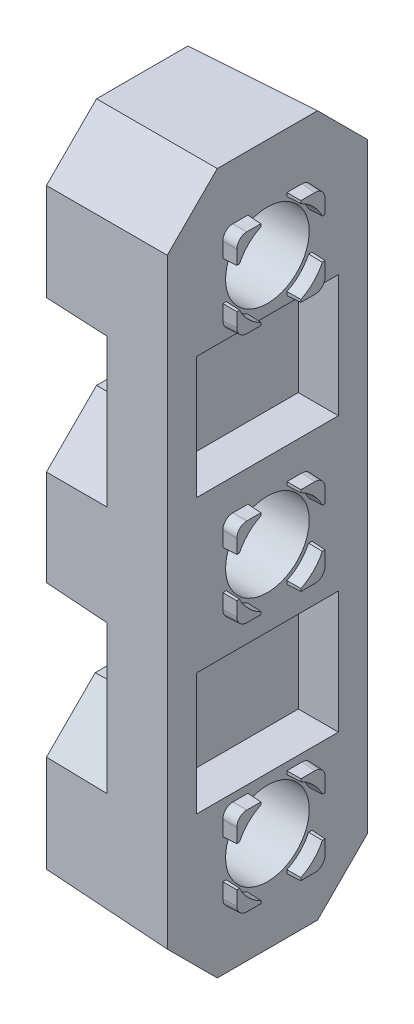
SolidWorks part; units mm, degrees
ref_plane "Front Plane" through (0, 0, 0) normal (0, 0, 1) x (1, 0, 0)
ref_plane "Top Plane" through (0, 0, 0) normal (0, 1, 0) x (1, 0, 0)
ref_plane "Right Plane" through (0, 0, 0) normal (1, 0, 0) x (0, 0, -1)
ref_plane "Plane1" through (88.9762, 0, 0) normal (1, 0, 0) x (0, 0, -1)
sketch "Sketch1" plane through (88.9762, 0, 0) normal (1, 0, 0) x (0, 0, -1)
  line L0 (7.8417, 8.8578) -> (17.5583, 8.8578)
  line L1 (17.5583, 8.8578) -> (17.5583, 43.9743)
  line L2 (17.5583, 43.9743) -> (7.8417, 43.9743)
  line L3 (7.8417, 43.9743) -> (7.8417, 8.8578)
extrude "Boss-Extrude1" add sketch "Sketch1" against normal blind 6.35
sketch "Sketch2" plane through (82.6262, 0, 0) normal (-1, 0, 0) x (0, 0, 1)
  line L0 (-7.8417, 36.5093) -> (-10.3153, 34.0358)
  line L1 (-10.3153, 34.0358) -> (-11.7, 34.0358)
  line L2 (-11.7, 34.0358) -> (-11.7, 31.3853)
  line L3 (-11.7, 31.3853) -> (-10.3802, 31.3853)
  line L4 (-10.3802, 31.3853) -> (-7.8417, 28.8468)
  line L5 (-7.8417, 28.8468) -> (-7.8417, 36.5093)
extrude "Cut-Extrude1" cut sketch "Sketch2" against normal blind 3.175
sketch "Sketch3" plane through (82.6262, 0, 0) normal (-1, 0, 0) x (0, 0, 1)
  line L0 (-7.8417, 23.9852) -> (-10.3802, 21.4468)
  line L1 (-10.3802, 21.4468) -> (-11.7, 21.4468)
  line L2 (-11.7, 21.4468) -> (-11.7, 18.7963)
  line L3 (-11.7, 18.7963) -> (-10.3153, 18.7963)
  line L4 (-10.3153, 18.7963) -> (-7.8417, 16.3228)
  line L5 (-7.8417, 16.3228) -> (-7.8417, 23.9852)
extrude "Cut-Extrude2" cut sketch "Sketch3" against normal blind 3.175
sketch "Sketch4" plane through (82.6262, 0, 0) normal (-1, 0, 0) x (0, 0, 1)
  line L0 (-17.5583, 16.3228) -> (-15.0847, 18.7963)
  line L1 (-15.0847, 18.7963) -> (-13.7, 18.7963)
  line L2 (-13.7, 18.7963) -> (-13.7, 21.4468)
  line L3 (-13.7, 21.4468) -> (-15.0198, 21.4468)
  line L4 (-15.0198, 21.4468) -> (-17.5583, 23.9852)
  line L5 (-17.5583, 23.9852) -> (-17.5583, 16.3228)
extrude "Cut-Extrude3" cut sketch "Sketch4" against normal blind 3.175
sketch "Sketch5" plane through (82.6262, 0, 0) normal (-1, 0, 0) x (0, 0, 1)
  line L0 (-17.5583, 28.8468) -> (-15.0198, 31.3853)
  line L1 (-15.0198, 31.3853) -> (-13.7, 31.3853)
  line L2 (-13.7, 31.3853) -> (-13.7, 34.0358)
  line L3 (-13.7, 34.0358) -> (-15.0847, 34.0358)
  line L4 (-15.0847, 34.0358) -> (-17.5583, 36.5093)
  line L5 (-17.5583, 36.5093) -> (-17.5583, 28.8468)
extrude "Cut-Extrude4" cut sketch "Sketch5" against normal blind 3.175
sketch "Sketch6" plane through (88.9762, 0, 0) normal (1, 0, 0) x (0, 0, -1)
  line L0 (11.7094, 24.3276) -> (11.7094, 24.1554)
  line L1 (11.7094, 24.1554) -> (10.4394, 24.1554)
  line L2 (10.4394, 24.1554) -> (10.4394, 25.4254)
  line L3 (10.4394, 25.4254) -> (10.6116, 25.4254)
  arc A0 (10.6116, 25.4254) -> (11.7094, 24.3276) centre (12.7, 26.416) ccw
extrude "Boss-Extrude2" add sketch "Sketch6" along normal blind 0.6858 draft 2
sketch "Sketch7" plane through (88.9762, 0, 0) normal (1, 0, 0) x (0, 0, -1)
  line L0 (14.7884, 25.4254) -> (14.9606, 25.4254)
  line L1 (14.9606, 25.4254) -> (14.9606, 24.1554)
  line L2 (14.9606, 24.1554) -> (13.6906, 24.1554)
  line L3 (13.6906, 24.1554) -> (13.6906, 24.3276)
  arc A0 (13.6906, 24.3276) -> (14.7884, 25.4254) centre (12.7, 26.416) ccw
extrude "Boss-Extrude3" add sketch "Sketch7" along normal blind 0.6858 draft 2
sketch "Sketch8" plane through (88.9762, 0, 0) normal (1, 0, 0) x (0, 0, -1)
  line L0 (13.6906, 28.5044) -> (13.6906, 28.6766)
  line L1 (13.6906, 28.6766) -> (14.9606, 28.6766)
  line L2 (14.9606, 28.6766) -> (14.9606, 27.4066)
  line L3 (14.9606, 27.4066) -> (14.7884, 27.4066)
  arc A0 (14.7884, 27.4066) -> (13.6906, 28.5044) centre (12.7, 26.416) ccw
extrude "Boss-Extrude4" add sketch "Sketch8" along normal blind 0.6858 draft 2
sketch "Sketch9" plane through (88.9762, 0, 0) normal (1, 0, 0) x (0, 0, -1)
  line L0 (10.6116, 27.4066) -> (10.4394, 27.4066)
  line L1 (10.4394, 27.4066) -> (10.4394, 28.6766)
  line L2 (10.4394, 28.6766) -> (11.7094, 28.6766)
  line L3 (11.7094, 28.6766) -> (11.7094, 28.5044)
  arc A0 (11.7094, 28.5044) -> (10.6116, 27.4066) centre (12.7, 26.416) ccw
extrude "Boss-Extrude5" add sketch "Sketch9" along normal blind 0.6858 draft 2
sketch "Sketch10" plane through (88.9762, 0, 0) normal (1, 0, 0) x (0, 0, -1)
  line L0 (11.7094, 37.0276) -> (11.7094, 36.8554)
  line L1 (11.7094, 36.8554) -> (10.4394, 36.8554)
  line L2 (10.4394, 36.8554) -> (10.4394, 38.1254)
  line L3 (10.4394, 38.1254) -> (10.6116, 38.1254)
  arc A0 (10.6116, 38.1254) -> (11.7094, 37.0276) centre (12.7, 39.116) ccw
extrude "Boss-Extrude6" add sketch "Sketch10" along normal blind 0.6858 draft 2
sketch "Sketch11" plane through (88.9762, 0, 0) normal (1, 0, 0) x (0, 0, -1)
  line L0 (14.7884, 38.1254) -> (14.9606, 38.1254)
  line L1 (14.9606, 38.1254) -> (14.9606, 36.8554)
  line L2 (14.9606, 36.8554) -> (13.6906, 36.8554)
  line L3 (13.6906, 36.8554) -> (13.6906, 37.0276)
  arc A0 (13.6906, 37.0276) -> (14.7884, 38.1254) centre (12.7, 39.116) ccw
extrude "Boss-Extrude7" add sketch "Sketch11" along normal blind 0.6858 draft 2
sketch "Sketch12" plane through (88.9762, 0, 0) normal (1, 0, 0) x (0, 0, -1)
  line L0 (13.6906, 41.2044) -> (13.6906, 41.3766)
  line L1 (13.6906, 41.3766) -> (14.9606, 41.3766)
  line L2 (14.9606, 41.3766) -> (14.9606, 40.1066)
  line L3 (14.9606, 40.1066) -> (14.7884, 40.1066)
  arc A0 (14.7884, 40.1066) -> (13.6906, 41.2044) centre (12.7, 39.116) ccw
extrude "Boss-Extrude8" add sketch "Sketch12" along normal blind 0.6858 draft 2
sketch "Sketch13" plane through (88.9762, 0, 0) normal (1, 0, 0) x (0, 0, -1)
  line L0 (10.6116, 40.1066) -> (10.4394, 40.1066)
  line L1 (10.4394, 40.1066) -> (10.4394, 41.3766)
  line L2 (10.4394, 41.3766) -> (11.7094, 41.3766)
  line L3 (11.7094, 41.3766) -> (11.7094, 41.2044)
  arc A0 (11.7094, 41.2044) -> (10.6116, 40.1066) centre (12.7, 39.116) ccw
extrude "Boss-Extrude9" add sketch "Sketch13" along normal blind 0.6858 draft 2
sketch "Sketch14" plane through (88.9762, 0, 0) normal (1, 0, 0) x (0, 0, -1)
  line L0 (11.7094, 11.6276) -> (11.7094, 11.4554)
  line L1 (11.7094, 11.4554) -> (10.4394, 11.4554)
  line L2 (10.4394, 11.4554) -> (10.4394, 12.7254)
  line L3 (10.4394, 12.7254) -> (10.6116, 12.7254)
  arc A0 (10.6116, 12.7254) -> (11.7094, 11.6276) centre (12.7, 13.716) ccw
extrude "Boss-Extrude10" add sketch "Sketch14" along normal blind 0.6858 draft 2
sketch "Sketch15" plane through (88.9762, 0, 0) normal (1, 0, 0) x (0, 0, -1)
  line L0 (14.7884, 12.7254) -> (14.9606, 12.7254)
  line L1 (14.9606, 12.7254) -> (14.9606, 11.4554)
  line L2 (14.9606, 11.4554) -> (13.6906, 11.4554)
  line L3 (13.6906, 11.4554) -> (13.6906, 11.6276)
  arc A0 (13.6906, 11.6276) -> (14.7884, 12.7254) centre (12.7, 13.716) ccw
extrude "Boss-Extrude11" add sketch "Sketch15" along normal blind 0.6858 draft 2
sketch "Sketch16" plane through (88.9762, 0, 0) normal (1, 0, 0) x (0, 0, -1)
  line L0 (13.6906, 15.8044) -> (13.6906, 15.9766)
  line L1 (13.6906, 15.9766) -> (14.9606, 15.9766)
  line L2 (14.9606, 15.9766) -> (14.9606, 14.7066)
  line L3 (14.9606, 14.7066) -> (14.7884, 14.7066)
  arc A0 (14.7884, 14.7066) -> (13.6906, 15.8044) centre (12.7, 13.716) ccw
extrude "Boss-Extrude12" add sketch "Sketch16" along normal blind 0.6858 draft 2
sketch "Sketch17" plane through (88.9762, 0, 0) normal (1, 0, 0) x (0, 0, -1)
  line L0 (10.6116, 14.7066) -> (10.4394, 14.7066)
  line L1 (10.4394, 14.7066) -> (10.4394, 15.9766)
  line L2 (10.4394, 15.9766) -> (11.7094, 15.9766)
  line L3 (11.7094, 15.9766) -> (11.7094, 15.8044)
  arc A0 (11.7094, 15.8044) -> (10.6116, 14.7066) centre (12.7, 13.716) ccw
extrude "Boss-Extrude13" add sketch "Sketch17" along normal blind 0.6858 draft 2
sketch "Sketch18" plane through (88.9762, 0, 0) normal (1, 0, 0) x (0, 0, -1)
  line L0 (9.1, 16.366) -> (16.3, 16.366)
  line L1 (16.3, 16.366) -> (16.3, 22.566)
  line L2 (16.3, 22.566) -> (9.1, 22.566)
  line L3 (9.1, 22.566) -> (9.1, 16.366)
extrude "Cut-Extrude5" cut sketch "Sketch18" against normal blind 2.032
sketch "Sketch19" plane through (88.9762, 0, 0) normal (1, 0, 0) x (0, 0, -1)
  line L0 (9.1, 36.466) -> (9.1, 30.266)
  line L1 (9.1, 30.266) -> (16.3, 30.266)
  line L2 (16.3, 30.266) -> (16.3, 36.466)
  line L3 (16.3, 36.466) -> (9.1, 36.466)
extrude "Cut-Extrude6" cut sketch "Sketch19" against normal blind 2.032
draft "Draft1" type of draft neutral plane draft angle 2.827 faces to draft 4 face at (84.2137, 30.116, -9.111) face at (84.2137, 22.716, -9.111) face at (84.2137, 22.716, -16.289) face at (84.2137, 30.116, -16.289) neutral plane through (82.6262, 0, 0) neutral plane normal (-1, 0, 0) parameters "D1"=2.827
draft "Draft2" type of draft neutral plane draft angle 2 faces to draft 16 face at (85.8012, 43.9743, -12.7) face at (84.2137, 35.2725, -9.0785) face at (84.2137, 34.0358, -11.0076) face at (84.2137, 31.3853, -10.9847) face at (84.2137, 21.4468, -10.9847) face at (84.2137, 18.7963, -11.0076) face at (84.2137, 17.5595, -9.0785) face at (84.7429, 26.416, -7.8417) face at (85.8012, 8.8578, -12.7) face at (84.2137, 17.5595, -16.3215) face at (84.2137, 18.7963, -14.3924) face at (84.2137, 21.4468, -14.4153) face at (84.2137, 31.3853, -14.4153) face at (84.2137, 34.0358, -14.3924) face at (84.2137, 35.2725, -16.3215) face at (84.7429, 26.416, -17.5583) neutral plane through (82.6262, 0, 0) neutral plane normal (-1, 0, 0) parameters "D1"=2
hole_wizard "Hole1" positions "Sketch21" profile "Sketch20" legacy
sketch "Sketch21" plane through (82.6262, 0, 0) normal (-1, 0, 0) x (0, 0, 1)
  point P0 (-12.7, 26.416)
  point P1 (-12.7, 13.716)
  point P2 (-12.7, 39.116)
sketch "Sketch20" plane through (82.6262, 26.416, -12.7) normal (0, 1, 0) x (0, 0, 1)
  line L0 (0, 0) -> (0, 7.0358)
  line L1 (0, 7.0358) -> (2.1209, 7.0358)
  line L2 (2.1209, 7.0358) -> (2.1209, 0)
  line L3 (2.1209, 0) -> (0, 0)
  line L4 (0, 110) -> (0, -10) construction
  dimension "Diameter" = 4.2418
  dimension "Depth" = 7.0358
chamfer "Chamfer1" distance 2.5369 angle 44.965 4 edges at (85.8012, 8.7469, -17.6691) (85.8012, 44.0851, -17.6691) (85.8012, 8.7469, -7.7309) (85.8012, 44.0851, -7.7309)
fillet "Fillet1" radius 0.508 12 edges at (89.3191, 41.3646, -10.4514) (89.3191, 15.9646, -10.4514) (89.3191, 11.4674, -14.9486) (89.3191, 24.1674, -10.4514) (89.3191, 41.3646, -14.9486) (89.3191, 24.1674, -14.9486) (89.3191, 11.4674, -10.4514) (89.3191, 28.6646, -14.9486) (89.3191, 15.9646, -14.9486) (89.3191, 36.8674, -10.4514) (89.3191, 36.8674, -14.9486) (89.3191, 28.6646, -10.4514)
